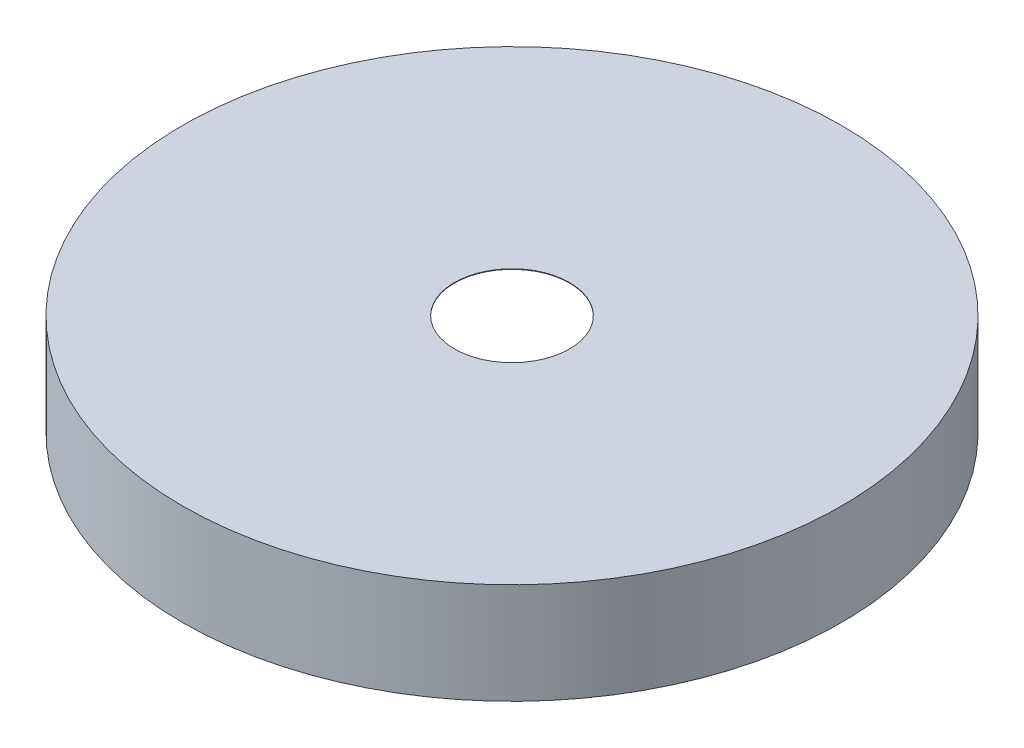
SolidWorks part; units mm, degrees
ref_plane "Front Plane" through (0, 0, 0) normal (0, 0, 1) x (1, 0, 0)
ref_plane "Top Plane" through (0, 0, 0) normal (0, 1, 0) x (1, 0, 0)
ref_plane "Right Plane" through (0, 0, 0) normal (1, 0, 0) x (0, 0, -1)
sketch "Sketch1" plane through (0, 0, 0) normal (0, 0, 1) x (1, 0, 0)
  line L0 (-160.02, 0) -> (-160.02, 49.022)
  line L2 (55, 0) -> (-55, 0) construction
  line L3 (-27.94, 48.768) -> (-157.48, 48.768)
  line L4 (-157.48, 0) -> (-157.48, 48.768)
  line L5 (0, -55) -> (0, 55) construction
  line L7 (-160.02, 49.022) -> (-27.94, 49.022)
  line L8 (-27.94, 49.022) -> (-27.94, 48.768)
  line L9 (-157.48, 0) -> (-160.02, 0)
  point P0 (0, 0)
  dimension "D1" = 160.02
  dimension "D2" = 49.022
  dimension "D3" = 0.254
  dimension "D4" = 2.54
  dimension "D5" = 27.94
ref_axis "Axis1" through (0, -2.54, 0) along (0, 1, 0)
revolve "Revolve1" add sketch "Sketch1" angle 360 about axis through (0, -2.54, 0) along (0, 1, 0)
